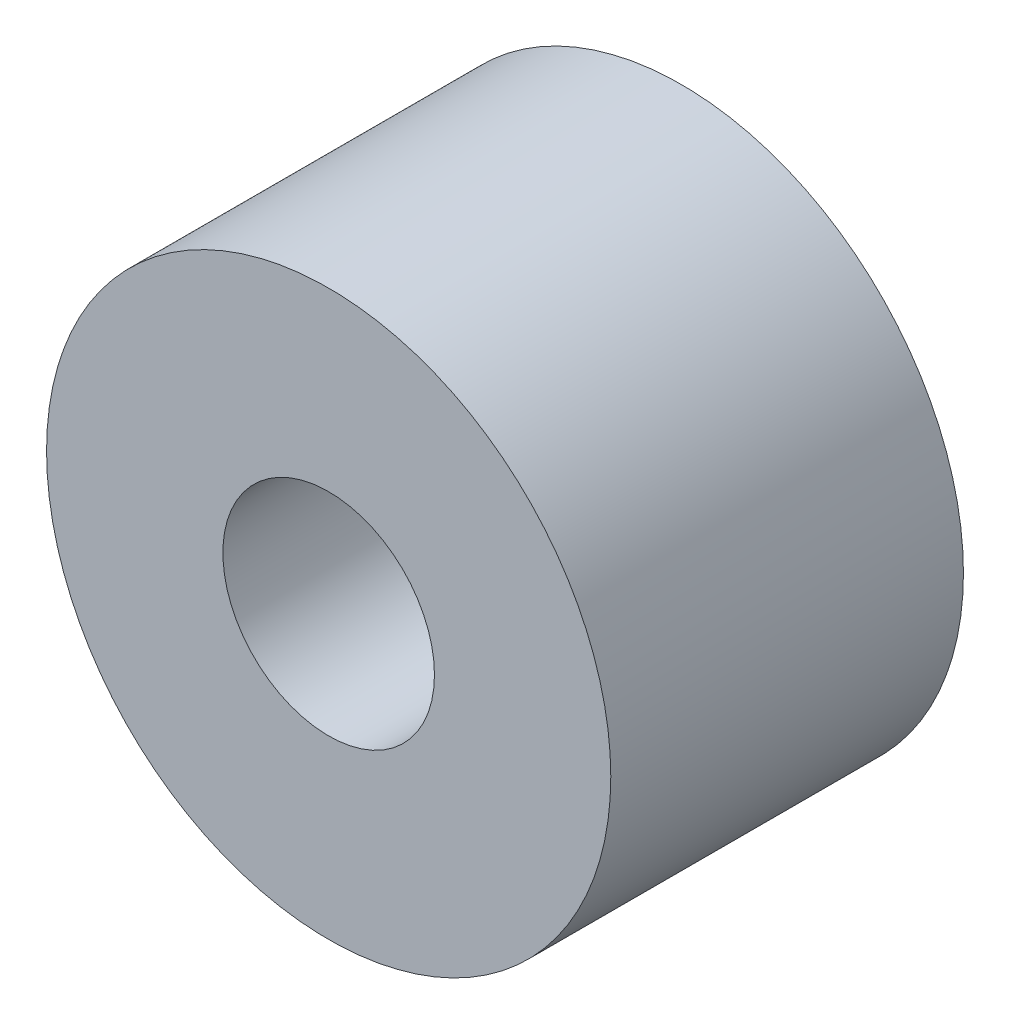
SolidWorks part; units mm, degrees
ref_plane "Front Plane" through (0, 0, 0) normal (0, 0, 1) x (1, 0, 0)
ref_plane "Top Plane" through (0, 0, 0) normal (0, 1, 0) x (1, 0, 0)
ref_plane "Right Plane" through (0, 0, 0) normal (1, 0, 0) x (0, 0, -1)
sketch "Sketch1" plane through (0, 0, 0) normal (0, 0, 1) x (1, 0, 0)
  circle A0 centre (0, 0) radius 4
  circle A1 centre (0, 0) radius 1.5
  dimension "D1" = 3
  dimension "D2" = 8
extrude "Boss-Extrude1" add sketch "Sketch1" along normal blind 5
